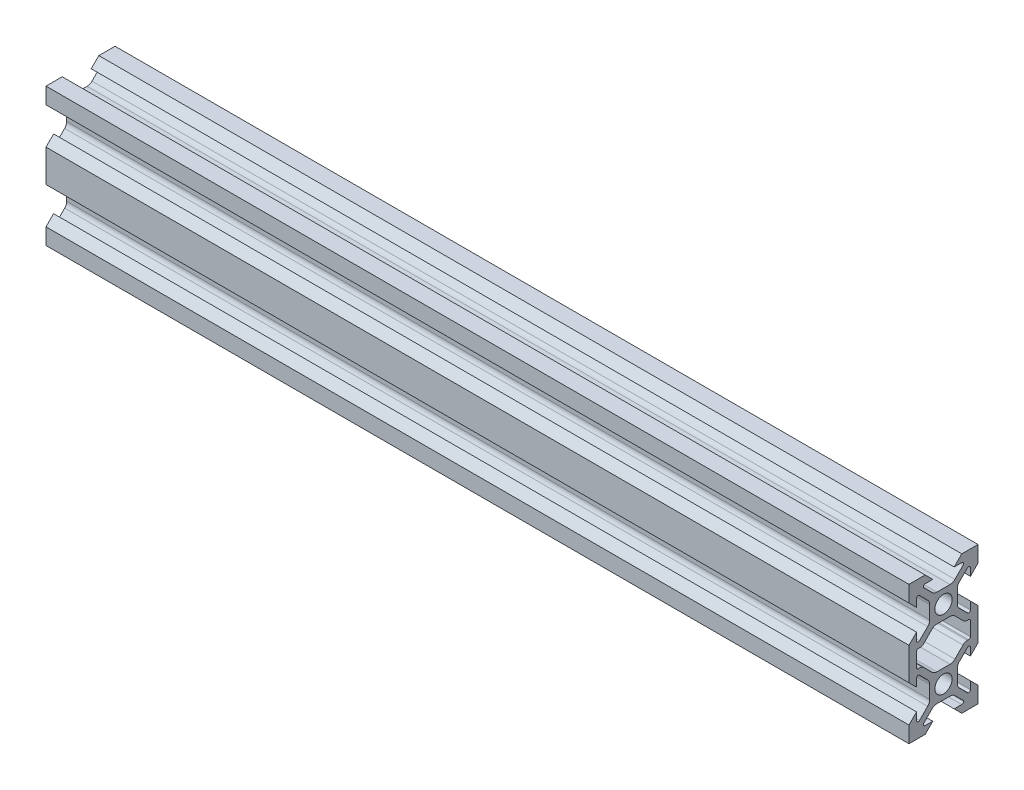
SolidWorks part; units mm, degrees
ref_plane "Front Plane" through (0, 0, 0) normal (0, 0, 1) x (1, 0, 0)
ref_plane "Top Plane" through (0, 0, 0) normal (0, 1, 0) x (1, 0, 0)
ref_plane "Right Plane" through (0, 0, 0) normal (1, 0, 0) x (0, 0, -1)
sketch "Sketch1" plane through (0, 0, 0) normal (1, 0, 0) x (0, 0, -1)
  line L0 (0, 0) -> (0, 10) construction
  line L1 (0, 10) -> (-10, 10) construction
  line L2 (-10, 10) -> (-10, 0) construction
  line L3 (-10, 0) -> (0, 0) construction
  line L4 (0, 0) -> (-10, 10) construction
  line L5 (-10, 10) -> (-10, 5.3)
  line L6 (-10, 5.3) -> (-7.8, 3.1)
  line L7 (-7.8, 3.1) -> (-7.8, 5.3201)
  line L8 (-6.9464, 5.6737) -> (-4.5858, 3.313)
  line L9 (-4, 1.8988) -> (-4, 0)
  line L10 (-10, 10) -> (-5.3, 10)
  line L11 (-5.3, 10) -> (-3.1, 7.8)
  line L12 (-3.1, 7.8) -> (-5.3201, 7.8)
  line L13 (-5.6737, 6.9464) -> (-3.313, 4.5858)
  line L14 (-1.8988, 4) -> (1.8988, 4)
  line L25 (5.6737, 6.9464) -> (3.313, 4.5858)
  line L26 (3.1, 7.8) -> (5.3201, 7.8)
  line L27 (5.3, 10) -> (3.1, 7.8)
  line L28 (10, 10) -> (5.3, 10)
  line L29 (4, 1.8988) -> (4, 0)
  line L40 (-7.8, -3.1) -> (-7.8, 3.1) construction
  line L41 (6.9464, 5.6737) -> (4.5858, 3.313)
  line L42 (7.8, 3.1) -> (7.8, 5.3201)
  line L43 (10, 5.3) -> (7.8, 3.1)
  line L44 (10, 10) -> (10, 5.3)
  line L48 (-5.6737, -6.9464) -> (-3.313, -4.5858)
  line L49 (-1.8988, -4) -> (1.8988, -4)
  line L50 (-10, -14.7) -> (-10, -5.3)
  line L51 (-10, -5.3) -> (-7.8, -3.1)
  line L52 (-7.8, -3.1) -> (-7.8, -5.3201)
  line L53 (-6.9464, -5.6737) -> (-4.5858, -3.313)
  line L54 (-4, -1.8988) -> (-4, 0)
  line L55 (-6.9464, -7.4737) -> (-7.3, -7.4737)
  line L56 (-10, 0) -> (-10, -10) construction
  line L57 (-10, -10) -> (0, -10) construction
  line L58 (4, -1.8988) -> (4, 0)
  line L59 (0, 0) -> (-10, -10) construction
  line L60 (-7.8, -7.9737) -> (-7.8, -12.0263)
  line L61 (7.8, -7.9737) -> (7.8, -12.0263)
  line L62 (6.9464, -7.4737) -> (7.3, -7.4737)
  line L63 (6.9464, -5.6737) -> (4.5858, -3.313)
  line L64 (7.8, -3.1) -> (7.8, -5.3201)
  line L65 (10, -5.3) -> (7.8, -3.1)
  line L66 (10, -14.7) -> (10, -5.3)
  line L67 (5.6737, -6.9464) -> (3.313, -4.5858)
  line L68 (0, 0) -> (0, -10) construction
  line L69 (5.6737, -13.0536) -> (3.313, -15.4142)
  line L70 (10, -14.7) -> (7.8, -16.9)
  line L71 (7.8, -16.9) -> (7.8, -14.6799)
  line L72 (6.9464, -14.3263) -> (4.5858, -16.687)
  line L73 (6.9464, -12.5263) -> (7.3, -12.5263)
  line L74 (4, -18.1012) -> (4, -20)
  line L75 (-6.9464, -12.5263) -> (-7.3, -12.5263)
  line L76 (-4, -18.1012) -> (-4, -20)
  line L77 (-6.9464, -14.3263) -> (-4.5858, -16.687)
  line L78 (-7.8, -16.9) -> (-7.8, -14.6799)
  line L79 (-10, -14.7) -> (-7.8, -16.9)
  line L80 (-1.8988, -16) -> (1.8988, -16)
  line L81 (-5.6737, -13.0536) -> (-3.313, -15.4142)
  line L82 (10, -30) -> (10, -25.3)
  line L83 (10, -25.3) -> (7.8, -23.1)
  line L84 (7.8, -23.1) -> (7.8, -25.3201)
  line L85 (6.9464, -25.6737) -> (4.5858, -23.313)
  line L86 (4, -21.8988) -> (4, -20)
  line L87 (10, -30) -> (5.3, -30)
  line L88 (5.3, -30) -> (3.1, -27.8)
  line L89 (3.1, -27.8) -> (5.3201, -27.8)
  line L90 (5.6737, -26.9464) -> (3.313, -24.5858)
  line L91 (-1.8988, -24) -> (1.8988, -24)
  line L92 (-5.6737, -26.9464) -> (-3.313, -24.5858)
  line L93 (-3.1, -27.8) -> (-5.3201, -27.8)
  line L94 (-5.3, -30) -> (-3.1, -27.8)
  line L95 (-10, -30) -> (-5.3, -30)
  line L96 (-4, -21.8988) -> (-4, -20)
  line L97 (-6.9464, -25.6737) -> (-4.5858, -23.313)
  line L98 (-7.8, -23.1) -> (-7.8, -25.3201)
  line L99 (-10, -25.3) -> (-7.8, -23.1)
  line L100 (-10, -30) -> (-10, -25.3)
  circle A0 centre (0, 0) radius 2.5
  arc A1 (-7.8, 5.3201) -> (-6.9464, 5.6737) centre (-7.3, 5.3201) cw
  arc A2 (-4.5858, 3.313) -> (-4, 1.8988) centre (-6, 1.8988) cw
  arc A3 (-5.3201, 7.8) -> (-5.6737, 6.9464) centre (-5.3201, 7.3) ccw
  arc A4 (-3.313, 4.5858) -> (-1.8988, 4) centre (-1.8988, 6) ccw
  arc A14 (-3.313, -4.5858) -> (-1.8988, -4) centre (-1.8988, -6) cw
  arc A15 (-7.8, -5.3201) -> (-6.9464, -5.6737) centre (-7.3, -5.3201) ccw
  arc A16 (-4.5858, -3.313) -> (-4, -1.8988) centre (-6, -1.8988) ccw
  arc A17 (3.313, 4.5858) -> (1.8988, 4) centre (1.8988, 6) cw
  arc A18 (5.3201, 7.8) -> (5.6737, 6.9464) centre (5.3201, 7.3) cw
  arc A19 (4.5858, 3.313) -> (4, 1.8988) centre (6, 1.8988) ccw
  arc A20 (7.8, 5.3201) -> (6.9464, 5.6737) centre (7.3, 5.3201) ccw
  arc A21 (-5.6737, -6.9464) -> (-6.9464, -7.4737) centre (-6.9464, -5.6737) cw
  arc A22 (-7.3, -7.4737) -> (-7.8, -7.9737) centre (-7.3, -7.9737) ccw
  arc A23 (7.3, -7.4737) -> (7.8, -7.9737) centre (7.3, -7.9737) cw
  arc A24 (5.6737, -6.9464) -> (6.9464, -7.4737) centre (6.9464, -5.6737) ccw
  arc A25 (4.5858, -3.313) -> (4, -1.8988) centre (6, -1.8988) cw
  arc A26 (7.8, -5.3201) -> (6.9464, -5.6737) centre (7.3, -5.3201) cw
  arc A27 (3.313, -4.5858) -> (1.8988, -4) centre (1.8988, -6) ccw
  arc A28 (3.313, -15.4142) -> (1.8988, -16) centre (1.8988, -14) cw
  arc A29 (7.8, -14.6799) -> (6.9464, -14.3263) centre (7.3, -14.6799) ccw
  arc A30 (4.5858, -16.687) -> (4, -18.1012) centre (6, -18.1012) ccw
  arc A31 (5.6737, -13.0536) -> (6.9464, -12.5263) centre (6.9464, -14.3263) cw
  arc A32 (7.3, -12.5263) -> (7.8, -12.0263) centre (7.3, -12.0263) ccw
  arc A33 (-7.3, -12.5263) -> (-7.8, -12.0263) centre (-7.3, -12.0263) cw
  arc A34 (-5.6737, -13.0536) -> (-6.9464, -12.5263) centre (-6.9464, -14.3263) ccw
  arc A35 (7.8, -25.3201) -> (6.9464, -25.6737) centre (7.3, -25.3201) cw
  arc A36 (4.5858, -23.313) -> (4, -21.8988) centre (6, -21.8988) cw
  arc A37 (5.3201, -27.8) -> (5.6737, -26.9464) centre (5.3201, -27.3) ccw
  arc A38 (3.313, -24.5858) -> (1.8988, -24) centre (1.8988, -26) ccw
  arc A39 (-4.5858, -16.687) -> (-4, -18.1012) centre (-6, -18.1012) cw
  arc A40 (-7.8, -14.6799) -> (-6.9464, -14.3263) centre (-7.3, -14.6799) cw
  arc A41 (-3.313, -15.4142) -> (-1.8988, -16) centre (-1.8988, -14) ccw
  arc A42 (-3.313, -24.5858) -> (-1.8988, -24) centre (-1.8988, -26) cw
  arc A43 (-5.3201, -27.8) -> (-5.6737, -26.9464) centre (-5.3201, -27.3) cw
  arc A44 (-4.5858, -23.313) -> (-4, -21.8988) centre (-6, -21.8988) ccw
  arc A45 (-7.8, -25.3201) -> (-6.9464, -25.6737) centre (-7.3, -25.3201) ccw
  circle A46 centre (0, -20) radius 2.5
  point P36 (0, 4)
  point P47 (-7.8, 0)
  point P49 (0, 0)
  point P70 (-7.8, -10)
  point P80 (0, -4)
  point P138 (10, -10)
  point P139 (7.8, -10)
  point P153 (0, -16)
  point P154 (0, -20)
  point P155 (-7.8, -20)
  point P156 (0, -24)
  dimension "D1" = 5
  dimension "D5" = 2
  dimension "D7" = 0.5
  dimension "D2" = 10
  dimension "D3" = 5.3
  dimension "D4" = 6
  dimension "D6" = 0.9
  dimension "D8" = 3.1
  dimension "D10" = 20
extrude "Boss-Extrude1" add sketch "Sketch1" along normal blind 250
